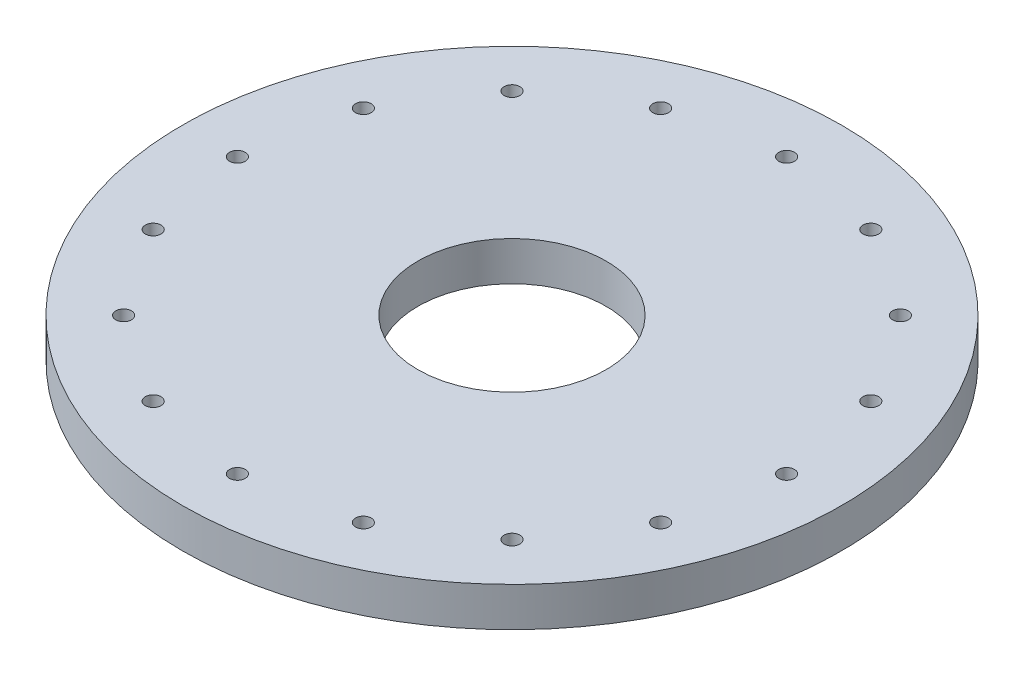
SolidWorks part; units mm, degrees
ref_plane "Front Plane" through (0, 0, 0) normal (0, 0, 1) x (1, 0, 0)
ref_plane "Top Plane" through (0, 0, 0) normal (0, 1, 0) x (1, 0, 0)
ref_plane "Right Plane" through (0, 0, 0) normal (1, 0, 0) x (0, 0, -1)
sketch "Sketch1" plane through (0, 0, 0) normal (0, 1, 0) x (1, 0, 0)
  circle A0 centre (0, 0) radius 12
  circle A2 centre (35, 0) radius 1
  circle A3 centre (32.3358, -13.3939) radius 1
  circle A4 centre (24.7487, -24.7487) radius 1
  circle A5 centre (13.3939, -32.3358) radius 1
  circle A6 centre (0, -35) radius 1
  circle A7 centre (-13.3939, -32.3358) radius 1
  circle A8 centre (-24.7487, -24.7487) radius 1
  circle A9 centre (-32.3358, -13.3939) radius 1
  circle A10 centre (-35, 0) radius 1
  circle A11 centre (-32.3358, 13.3939) radius 1
  circle A12 centre (-24.7487, 24.7487) radius 1
  circle A13 centre (-13.3939, 32.3358) radius 1
  circle A14 centre (0, 35) radius 1
  circle A15 centre (13.3939, 32.3358) radius 1
  circle A16 centre (24.7487, 24.7487) radius 1
  circle A17 centre (32.3358, 13.3939) radius 1
  circle A18 centre (0, 0) radius 42
  point P39 (0, 0)
  dimension "D1" = 16
extrude "Boss-Extrude1" add sketch "Sketch1" along normal blind 5
